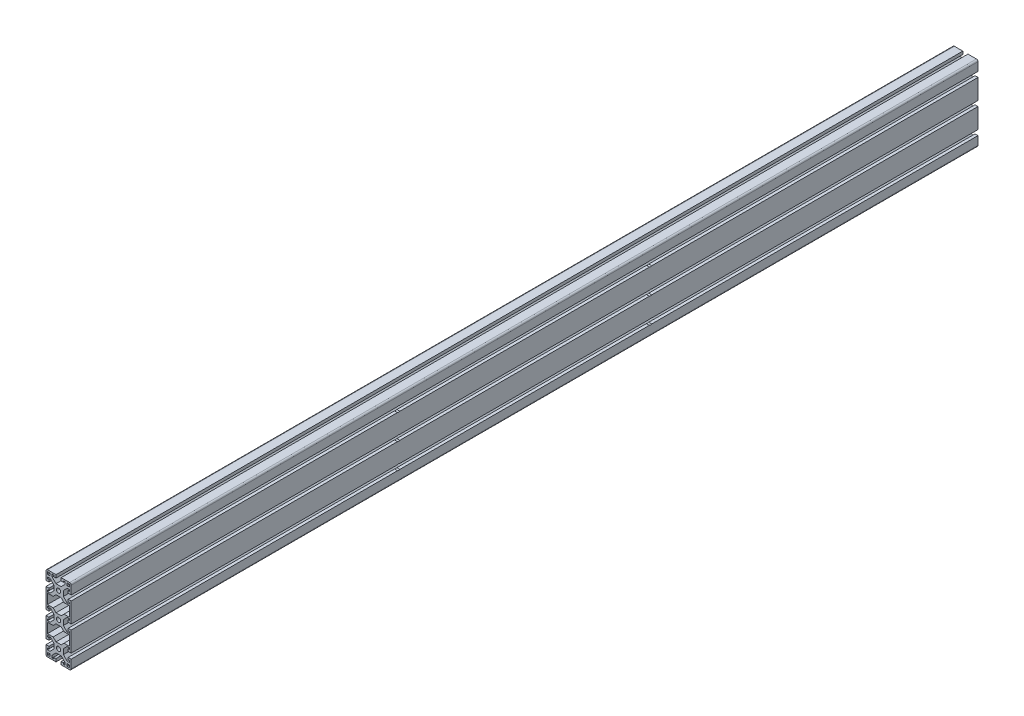
SolidWorks part; units mm, degrees
material "6063-T6"
ref_plane "Front Plane" through (0, 0, 0) normal (0, 0, 1) x (1, 0, 0)
ref_plane "Top Plane" through (0, 0, 0) normal (0, 1, 0) x (1, 0, 0)
ref_plane "Right Plane" through (0, 0, 0) normal (1, 0, 0) x (0, 0, -1)
sketch "Sketch1" plane through (0, 0, 0) normal (0, 1, 0) x (1, 0, 0)
  line L0 (0, -720) -> (0, 720)
  dimension "D1" = 1440
other "40 series TS40-120LM(1)"
ref_plane "Plane1" through (0, 0, 720) normal (0, 0, -1) x (-1, 0, 0)
sketch "Sketch2" plane through (0, 0, 720) normal (0, 0, -1) x (-1, 0, 0)
  line L0 (15.3, -35.9) -> (20, -35.9)
  line L1 (3.35, 0) -> (7.6, 0) construction
  line L2 (7.6, 4.1) -> (7.6, -4.1)
  line L3 (7.6, -4.1) -> (13.6, -10.1)
  line L4 (13.6, -10.1) -> (17.65, -10.1)
  line L5 (17.65, -10.1) -> (17.65, -7.6)
  line L6 (17.65, -7.6) -> (15.3, -7.6)
  line L7 (15.3, -7.6) -> (15.3, -4.1)
  line L8 (15.3, -4.1) -> (20, -4.1)
  line L9 (20, -4.1) -> (20, -35.9)
  line L10 (0, -3.35) -> (0, -7.6) construction
  line L11 (-4.1, -7.6) -> (4.1, -7.6)
  line L12 (4.1, -7.6) -> (8.6, -12.1)
  line L13 (8.6, -12.1) -> (17.65, -12.1)
  line L14 (17.65, -12.1) -> (17.65, -27.9)
  line L15 (20, -20) -> (0, 0) construction
  line L16 (17.65, -20) -> (20, -20) construction
  line L17 (15.3, -32.4) -> (15.3, -35.9)
  line L18 (17.65, -32.4) -> (15.3, -32.4)
  line L19 (17.65, -29.9) -> (17.65, -32.4)
  line L20 (13.6, -29.9) -> (17.65, -29.9)
  line L21 (8.6, -27.9) -> (17.65, -27.9)
  line L22 (7.6, -35.9) -> (13.6, -29.9)
  line L23 (7.6, -44.1) -> (7.6, -35.9)
  line L24 (4.1, -32.4) -> (8.6, -27.9)
  line L25 (-4.1, -32.4) -> (4.1, -32.4)
  line L26 (3.35, -40) -> (7.6, -40) construction
  line L27 (15.3, -44.1) -> (20, -44.1)
  line L28 (15.3, -47.6) -> (15.3, -44.1)
  line L29 (17.65, -47.6) -> (15.3, -47.6)
  line L30 (17.65, -50.1) -> (17.65, -47.6)
  line L31 (13.6, -50.1) -> (17.65, -50.1)
  line L32 (7.6, -44.1) -> (13.6, -50.1)
  line L33 (0, -40) -> (19.2678, -59.2678) construction
  line L34 (20, -57.5) -> (20, -44.1)
  line L35 (17.5, -60) -> (4.1, -60)
  line L36 (4.1, -55.3) -> (4.1, -60)
  line L37 (7.6, -55.3) -> (4.1, -55.3)
  line L38 (7.6, -57.65) -> (7.6, -55.3)
  line L39 (10.1, -57.65) -> (7.6, -57.65)
  line L40 (10.1, -53.6) -> (10.1, -57.65)
  line L41 (4.1, -47.6) -> (10.1, -53.6)
  line L42 (4.1, -47.6) -> (-4.1, -47.6)
  line L43 (0, -40) -> (-19.2678, -59.2678) construction
  line L44 (-3.35, -40) -> (-7.6, -40) construction
  line L45 (-17.65, -20) -> (-20, -20) construction
  line L46 (-20, -20) -> (0, 0) construction
  line L47 (-3.35, 0) -> (-7.6, 0) construction
  line L48 (-4.1, -47.6) -> (-10.1, -53.6)
  line L49 (-10.1, -53.6) -> (-10.1, -57.65)
  line L50 (-10.1, -57.65) -> (-7.6, -57.65)
  line L51 (-7.6, -57.65) -> (-7.6, -55.3)
  line L52 (-7.6, -55.3) -> (-4.1, -55.3)
  line L53 (-4.1, -55.3) -> (-4.1, -60)
  line L54 (-17.5, -60) -> (-4.1, -60)
  line L55 (-20, -57.5) -> (-20, -44.1)
  line L56 (-7.6, -44.1) -> (-13.6, -50.1)
  line L57 (-13.6, -50.1) -> (-17.65, -50.1)
  line L58 (-17.65, -50.1) -> (-17.65, -47.6)
  line L59 (-17.65, -47.6) -> (-15.3, -47.6)
  line L60 (-15.3, -47.6) -> (-15.3, -44.1)
  line L61 (-15.3, -44.1) -> (-20, -44.1)
  line L62 (-4.1, -32.4) -> (-8.6, -27.9)
  line L63 (-7.6, -44.1) -> (-7.6, -35.9)
  line L64 (-7.6, -35.9) -> (-13.6, -29.9)
  line L65 (-8.6, -27.9) -> (-17.65, -27.9)
  line L66 (-13.6, -29.9) -> (-17.65, -29.9)
  line L67 (-17.65, -29.9) -> (-17.65, -32.4)
  line L68 (-17.65, -32.4) -> (-15.3, -32.4)
  line L69 (-15.3, -32.4) -> (-15.3, -35.9)
  line L70 (-17.65, -12.1) -> (-17.65, -27.9)
  line L71 (-8.6, -12.1) -> (-17.65, -12.1)
  line L72 (-4.1, -7.6) -> (-8.6, -12.1)
  line L73 (-20, -4.1) -> (-20, -35.9)
  line L74 (-15.3, -4.1) -> (-20, -4.1)
  line L75 (-15.3, -7.6) -> (-15.3, -4.1)
  line L76 (-17.65, -7.6) -> (-15.3, -7.6)
  line L77 (-17.65, -10.1) -> (-17.65, -7.6)
  line L78 (-13.6, -10.1) -> (-17.65, -10.1)
  line L79 (-7.6, -4.1) -> (-13.6, -10.1)
  line L80 (-7.6, 4.1) -> (-7.6, -4.1)
  line L81 (-15.3, -35.9) -> (-20, -35.9)
  line L82 (-20, 20) -> (0, 0) construction
  line L83 (-17.65, 20) -> (-20, 20) construction
  line L84 (-3.35, 40) -> (-7.6, 40) construction
  line L85 (0, 40) -> (-19.2678, 59.2678) construction
  line L86 (0, 40) -> (19.2678, 59.2678) construction
  line L87 (3.35, 40) -> (7.6, 40) construction
  line L88 (17.65, 20) -> (20, 20) construction
  line L89 (20, 20) -> (0, 0) construction
  line L90 (0, 3.35) -> (0, 7.6) construction
  line L91 (-15.3, 35.9) -> (-20, 35.9)
  line L92 (-7.6, 4.1) -> (-13.6, 10.1)
  line L93 (-13.6, 10.1) -> (-17.65, 10.1)
  line L94 (-17.65, 10.1) -> (-17.65, 7.6)
  line L95 (-17.65, 7.6) -> (-15.3, 7.6)
  line L96 (-15.3, 7.6) -> (-15.3, 4.1)
  line L97 (-15.3, 4.1) -> (-20, 4.1)
  line L98 (-20, 4.1) -> (-20, 35.9)
  line L99 (-4.1, 7.6) -> (-8.6, 12.1)
  line L100 (-8.6, 12.1) -> (-17.65, 12.1)
  line L101 (-17.65, 12.1) -> (-17.65, 27.9)
  line L102 (-15.3, 32.4) -> (-15.3, 35.9)
  line L103 (-17.65, 32.4) -> (-15.3, 32.4)
  line L104 (-17.65, 29.9) -> (-17.65, 32.4)
  line L105 (-13.6, 29.9) -> (-17.65, 29.9)
  line L106 (-8.6, 27.9) -> (-17.65, 27.9)
  line L107 (-7.6, 35.9) -> (-13.6, 29.9)
  line L108 (-7.6, 44.1) -> (-7.6, 35.9)
  line L109 (-4.1, 32.4) -> (-8.6, 27.9)
  line L110 (-15.3, 44.1) -> (-20, 44.1)
  line L111 (-15.3, 47.6) -> (-15.3, 44.1)
  line L112 (-17.65, 47.6) -> (-15.3, 47.6)
  line L113 (-17.65, 50.1) -> (-17.65, 47.6)
  line L114 (-13.6, 50.1) -> (-17.65, 50.1)
  line L115 (-7.6, 44.1) -> (-13.6, 50.1)
  line L116 (-20, 57.5) -> (-20, 44.1)
  line L117 (-17.5, 60) -> (-4.1, 60)
  line L118 (-4.1, 55.3) -> (-4.1, 60)
  line L119 (-7.6, 55.3) -> (-4.1, 55.3)
  line L120 (-7.6, 57.65) -> (-7.6, 55.3)
  line L121 (-10.1, 57.65) -> (-7.6, 57.65)
  line L122 (-10.1, 53.6) -> (-10.1, 57.65)
  line L123 (-4.1, 47.6) -> (-10.1, 53.6)
  line L124 (4.1, 47.6) -> (-4.1, 47.6)
  line L125 (4.1, 47.6) -> (10.1, 53.6)
  line L126 (10.1, 53.6) -> (10.1, 57.65)
  line L127 (10.1, 57.65) -> (7.6, 57.65)
  line L128 (7.6, 57.65) -> (7.6, 55.3)
  line L129 (7.6, 55.3) -> (4.1, 55.3)
  line L130 (4.1, 55.3) -> (4.1, 60)
  line L131 (17.5, 60) -> (4.1, 60)
  line L132 (20, 57.5) -> (20, 44.1)
  line L133 (7.6, 44.1) -> (13.6, 50.1)
  line L134 (13.6, 50.1) -> (17.65, 50.1)
  line L135 (17.65, 50.1) -> (17.65, 47.6)
  line L136 (17.65, 47.6) -> (15.3, 47.6)
  line L137 (15.3, 47.6) -> (15.3, 44.1)
  line L138 (15.3, 44.1) -> (20, 44.1)
  line L139 (-4.1, 32.4) -> (4.1, 32.4)
  line L140 (4.1, 32.4) -> (8.6, 27.9)
  line L141 (7.6, 44.1) -> (7.6, 35.9)
  line L142 (7.6, 35.9) -> (13.6, 29.9)
  line L143 (8.6, 27.9) -> (17.65, 27.9)
  line L144 (13.6, 29.9) -> (17.65, 29.9)
  line L145 (17.65, 29.9) -> (17.65, 32.4)
  line L146 (17.65, 32.4) -> (15.3, 32.4)
  line L147 (15.3, 32.4) -> (15.3, 35.9)
  line L148 (17.65, 12.1) -> (17.65, 27.9)
  line L149 (8.6, 12.1) -> (17.65, 12.1)
  line L150 (4.1, 7.6) -> (8.6, 12.1)
  line L151 (-4.1, 7.6) -> (4.1, 7.6)
  line L152 (20, 4.1) -> (20, 35.9)
  line L153 (15.3, 4.1) -> (20, 4.1)
  line L154 (15.3, 7.6) -> (15.3, 4.1)
  line L155 (17.65, 7.6) -> (15.3, 7.6)
  line L156 (17.65, 10.1) -> (17.65, 7.6)
  line L157 (13.6, 10.1) -> (17.65, 10.1)
  line L158 (7.6, 4.1) -> (13.6, 10.1)
  line L159 (15.3, 35.9) -> (20, 35.9)
  line L161 (13.6, -53.6) -> (17.5, -53.6)
  line L162 (13.6, -53.6) -> (13.6, -57.5)
  line L163 (13.6, -57.5) -> (17.5, -57.5)
  line L164 (17.5, -53.6) -> (17.5, -57.5)
  line L165 (-17.5, -57.5) -> (-13.6, -57.5)
  line L166 (-17.5, -57.5) -> (-17.5, -53.6)
  line L167 (-17.5, -53.6) -> (-13.6, -53.6)
  line L168 (-13.6, -57.5) -> (-13.6, -53.6)
  line L169 (-17.5, 57.5) -> (-13.6, 57.5)
  line L170 (-17.5, 57.5) -> (-17.5, 53.6)
  line L171 (-17.5, 53.6) -> (-13.6, 53.6)
  line L172 (-13.6, 57.5) -> (-13.6, 53.6)
  line L173 (17.5, 57.5) -> (13.6, 57.5)
  line L174 (17.5, 57.5) -> (17.5, 53.6)
  line L175 (17.5, 53.6) -> (13.6, 53.6)
  line L176 (13.6, 57.5) -> (13.6, 53.6)
  arc A0 (0, -43.35) -> (0, -36.65) centre (0, -40) ccw
  arc A1 (3.35, 0) -> (-3.35, 0) centre (0, 0) cw
  arc A2 (17.5, -60) -> (20, -57.5) centre (17.5, -57.5) ccw
  arc A3 (-17.5, -60) -> (-20, -57.5) centre (-17.5, -57.5) cw
  arc A4 (0, -43.35) -> (0, -36.65) centre (0, -40) cw
  arc A5 (0, 43.35) -> (0, 36.65) centre (0, 40) ccw
  arc A6 (-17.5, 60) -> (-20, 57.5) centre (-17.5, 57.5) ccw
  arc A7 (17.5, 60) -> (20, 57.5) centre (17.5, 57.5) cw
  arc A8 (3.35, 0) -> (-3.35, 0) centre (0, 0) ccw
  arc A9 (0, 43.35) -> (0, 36.65) centre (0, 40) cw
  point P19 (17.65, -4.1)
  point P65 (0, -47.6)
  point P79 (0, -32.4)
  point P196 (0, 32.4)
  point P197 (0, 47.6)
  point P201 (20, -60)
  point P202 (-20, -60)
  point P203 (20, -40)
  point P204 (-20, -40)
  point P205 (20, -20)
  point P206 (0, -60)
  point P207 (0, -40)
  point P208 (-20, -20)
  point P209 (-20, 0)
  point P210 (20, 0)
  point P211 (20, 40)
  point P212 (0, 0)
  point P213 (-20, 20)
  point P214 (20, 20)
  point P215 (-20, 40)
  point P216 (0, 40)
  point P217 (20, 60)
  point P218 (0, 60)
  point P219 (-20, 60)
  point P220 (0, 20)
  point P221 (0, -20)
  point P222 (0, 0)
  dimension "D2" = 4.1
  dimension "D4" = 12.4
  dimension "D9" = 2.5
  dimension "D3" = 3.35
  dimension "D5" = 20
  dimension "D10" = 20
  dimension "D6" = 10.1
  dimension "D8" = 2
  dimension "D11" = 2.5
  dimension "D7" = 4.7
hole_wizard "M8x1.25 Tapped Hole1" positions "Sketch3" profile "Sketch4" tap size "M8x1.25" standard "ANSI Metric"
sketch "Sketch3" plane through (0, 0, 720) normal (0, 0, 1) x (1, 0, 0)
  point P0 (0, 40)
  point P3 (0, 0)
  point P6 (0, -40)
sketch "Sketch4" plane through (0, 40, 720) normal (1, 0, 0) x (0, -1, 0)
  line L0 (0, 0) -> (0, 32.0429)
  line L1 (0, 32.0429) -> (3.4, 30)
  line L2 (3.4, 30) -> (3.4, 0)
  line L5 (3.4, 0) -> (0, 0)
  line L10 (0, 32.0429) -> (-3.4, 30) construction
  line L11 (0, -6.35) -> (0, 107.95) construction
  dimension "Tap Drill Dia." = 6.8
  dimension "Tap Drill Depth" = 30
  dimension "Drill Angle" = 118
cosmetic thread "Hole Thread1" parameters "D1"=25, "D2"=8
cosmetic thread "Hole Thread2" parameters "D1"=25, "D2"=8
cosmetic thread "Hole Thread5" parameters "D1"=25, "D2"=8
hole_wizard "M8x1.25 Tapped Hole2" positions "Sketch5" profile "Sketch6" tap size "M8x1.25" standard "ANSI Metric"
sketch "Sketch5" plane through (0, 0, -720) normal (0, 0, -1) x (-1, 0, 0)
  point P0 (0, 40)
  point P3 (0, 0)
  point P6 (0, -40)
sketch "Sketch6" plane through (0, 40, -720) normal (1, 0, 0) x (0, 1, 0)
  line L0 (0, 0) -> (0, 32.0429)
  line L1 (0, 32.0429) -> (3.4, 30)
  line L2 (3.4, 30) -> (3.4, 0)
  line L5 (3.4, 0) -> (0, 0)
  line L10 (0, 32.0429) -> (-3.4, 30) construction
  line L11 (0, -6.35) -> (0, 107.95) construction
  dimension "Tap Drill Dia." = 6.8
  dimension "Tap Drill Depth" = 30
  dimension "Drill Angle" = 118
cosmetic thread "Hole Thread3" parameters "D1"=25, "D2"=8
cosmetic thread "Hole Thread4" parameters "D1"=25, "D2"=8
hole_wizard "M8 Clearance Hole1" positions "Sketch7" profile "Sketch8" hole size "M8" standard "ANSI Metric" end condition through all
sketch "Sketch7" plane through (-20, 0, 0) normal (-1, 0, 0) x (0, 0, 1)
  line L0 (-200, 40) -> (-200, -40)
  line L3 (-200, 0) -> (200, 0)
  line L6 (200, 40) -> (200, -40)
  point P1 (-200, 40)
  point P2 (-200, -40)
  point P11 (200, 40)
  point P12 (200, -40)
  point P19 (-200, 0)
  point P22 (200, 0)
  dimension "D1" = 80
  dimension "D2" = 400
sketch "Sketch8" plane through (-20, 40, -200) normal (0, 1, 0) x (0, 0, 1)
  line L0 (0, 0) -> (0, 40)
  line L1 (0, 40) -> (4.5, 40)
  line L2 (4.5, 40) -> (4.5, 0)
  line L5 (4.5, 0) -> (0, 0)
  line L11 (0, -6.35) -> (0, 107.95) construction
  dimension "Thru Hole Dia." = 9
  dimension "Thru Hole Depth" = 40
